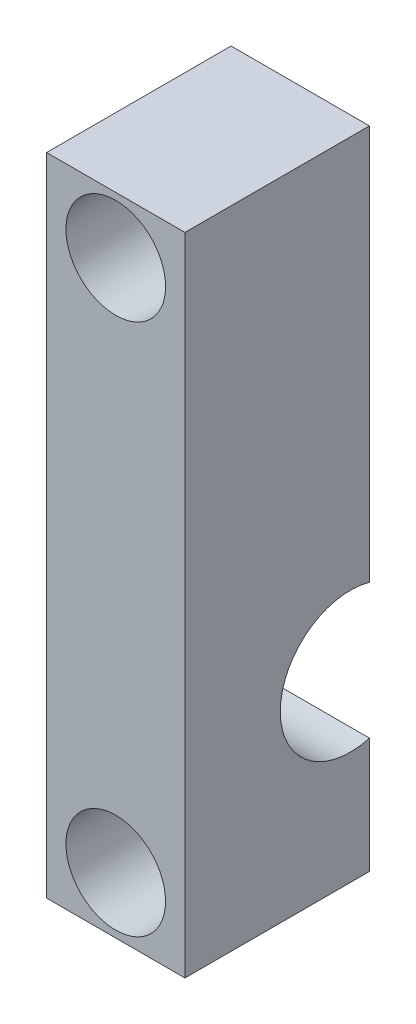
SolidWorks part; units mm, degrees
ref_plane "Front Plane" through (0, 0, 0) normal (0, 0, 1) x (1, 0, 0)
ref_plane "Top Plane" through (0, 0, 0) normal (0, 1, 0) x (1, 0, 0)
ref_plane "Right Plane" through (0, 0, 0) normal (1, 0, 0) x (0, 0, -1)
sketch "Sketch1" plane through (0, 0, 0) normal (0, 0, 1) x (1, 0, 0)
  line L1 (-6.6461, 31.0151) -> (2.8789, 31.0151)
  line L2 (-6.6461, 31.0151) -> (-6.6461, -13.4349)
  line L3 (-6.6461, -13.4349) -> (2.8789, -13.4349)
  line L4 (2.8789, 31.0151) -> (2.8789, -13.4349)
  line L5 (-6.6461, 31.0151) -> (2.8789, -13.4349) construction
  line L6 (-6.6461, -13.4349) -> (2.8789, 31.0151) construction
  point P0 (0, 0)
  dimension "D1" = 44.45
  dimension "D2" = 9.525
extrude "Boss-Extrude1" add sketch "Sketch1" along normal blind 12.7
sketch "Sketch2" plane through (0, 0, 12.7) normal (0, 0, 1) x (1, 0, 0)
  line L0 (2.8789, 31.0151) -> (-6.6461, 31.0151) construction
  line L1 (2.8789, -13.4349) -> (2.8789, 31.0151) construction
  line L2 (-6.6461, -13.4349) -> (2.8789, -13.4349) construction
  circle A0 centre (-1.8836, 27.1162) radius 3.429
  circle A1 centre (-1.8836, -9.536) radius 3.429
  dimension "D1" = 6.858
  dimension "D2" = 3.8989
  dimension "D3" = 3.8989
  dimension "D4" = 4.7625
extrude "Cut-Extrude1" cut sketch "Sketch2" against normal blind 6.35
sketch "Sketch3" plane through (0, 0, 6.35) normal (0, 0, 1) x (1, 0, 0)
  circle A0 centre (-1.8836, 27.1162) radius 1.397
  circle A1 centre (-1.8836, 27.1162) radius 3.429 construction
  circle A2 centre (-1.8836, -9.536) radius 1.397
  circle A3 centre (-1.8836, -9.536) radius 3.429 construction
  dimension "D1" = 2.794
extrude "Cut-Extrude2" cut sketch "Sketch3" against normal through all
sketch "Sketch4" plane through (-6.6461, 0, 0) normal (-1, 0, 0) x (0, 0, 1)
  circle A0 centre (1.3123, -0.8412) radius 4.826
  circle A1 centre (1.3123, -0.8412) radius 4.7625 construction
  circle A2 centre (1.3123, -0.8412) radius 4.7625
  dimension "D1" = 9.652
extrude "Cut-Extrude3" cut sketch "Sketch4" against normal through all
